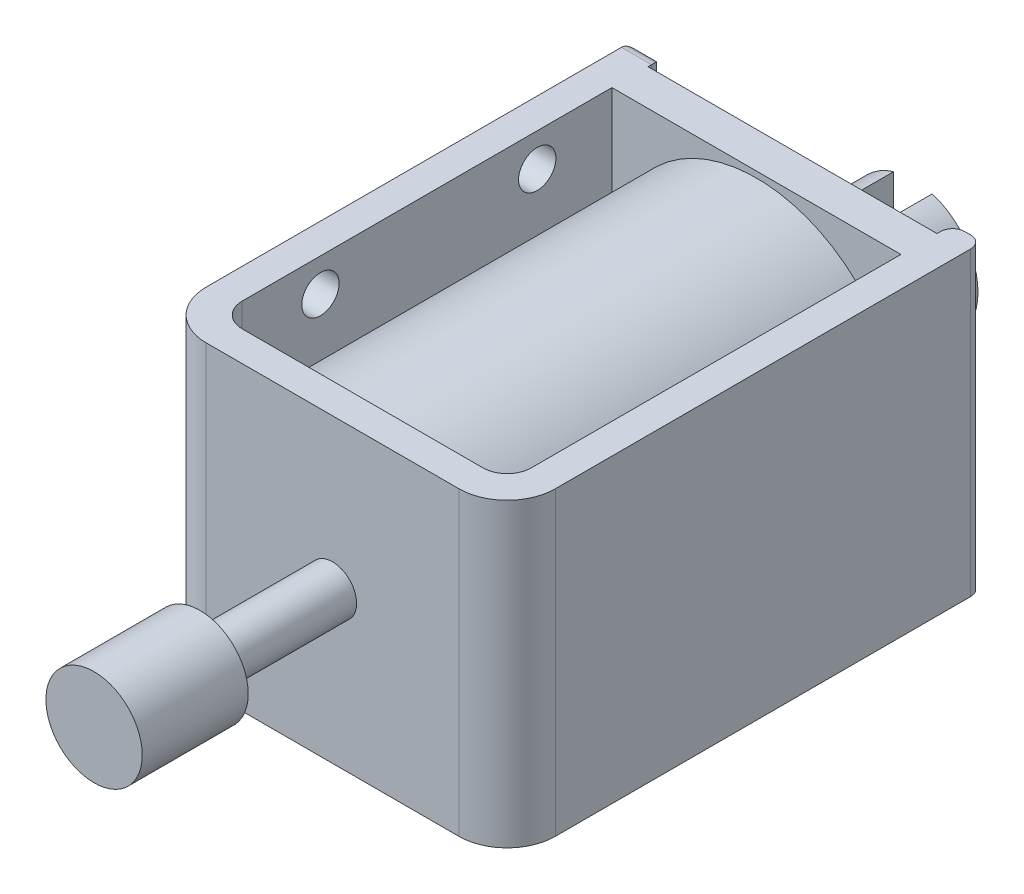
SolidWorks part; units mm, degrees
ref_plane "Front Plane" through (0, 0, 0) normal (0, 0, 1) x (1, 0, 0)
ref_plane "Top Plane" through (0, 0, 0) normal (0, 1, 0) x (1, 0, 0)
ref_plane "Right Plane" through (0, 0, 0) normal (1, 0, 0) x (0, 0, -1)
sketch "Sketch1" plane through (0, 0, 0) normal (0, 1, 0) x (1, 0, 0)
  line L0 (-21.1094, 9.1992) -> (-18.6094, 9.1992)
  line L1 (-18.6094, 9.1992) -> (-18.6094, 7.9023)
  line L2 (-18.6094, 7.9023) -> (5.3906, 7.9023)
  line L3 (5.3906, 7.9023) -> (5.3906, 9.1992)
  line L4 (5.3906, 9.1992) -> (7.8906, 9.1992)
  line L5 (7.8906, 9.1992) -> (7.8906, -30.3008)
  line L6 (7.8906, -30.3008) -> (-21.1094, -30.3008)
  line L7 (-21.1094, -30.3008) -> (-21.1094, 9.1992)
  line L8 (-18.6094, 4.9023) -> (5.3906, 4.9023)
  line L11 (-18.6094, 4.9023) -> (-18.6094, -27.8008)
  line L12 (-18.6094, -27.8008) -> (5.3906, -27.8008)
  line L13 (5.3906, -27.8008) -> (5.3906, 4.9023)
  dimension "D1" = 2.5
  dimension "D2" = 39.5
  dimension "D3" = 29
  dimension "D4" = 2.5
  dimension "D5" = 3
  dimension "D6" = 2.5
  dimension "D7" = 39.5
extrude "Boss-Extrude1" add sketch "Sketch1" along normal blind 25
sketch "Sketch3" plane through (0, 0, -4.9023) normal (0, 0, 1) x (1, 0, 0)
  line L0 (-6.6094, 25) -> (-6.6094, 0) construction
  line L1 (-21.1094, 25) -> (7.8906, 25) construction
  line L2 (-21.1094, 0) -> (7.8906, 0) construction
  circle A0 centre (-6.6094, 12.5) radius 12
  dimension "D1" = 24
extrude "Boss-Extrude7" add sketch "Sketch3" along normal up to surface (32.7031 mm away) separate body up to face at (-6.6094, 12.5, 27.8008)
sketch "Sketch4" plane through (0, 0, 30.3008) normal (0, 0, 1) x (1, 0, 0)
  line L0 (-21.1094, 25) -> (7.8906, 0) construction
  line L1 (-21.1094, 0) -> (7.8906, 0) construction
  line L2 (7.8906, 25) -> (-21.1094, 0) construction
  line L3 (-21.1094, 25) -> (-21.1094, 0) construction
  circle A0 centre (-6.6094, 12.5) radius 2
extrude "Boss-Extrude8" add sketch "Sketch4" along normal blind 11
sketch "Sketch5" plane through (0, 0, 41.3008) normal (0, 0, 1) x (1, 0, 0)
  circle A0 centre (-6.6094, 12.5) radius 4
extrude "Boss-Extrude9" add sketch "Sketch5" along normal blind 8.8
sketch "Sketch6" plane through (-21.1094, 0, 0) normal (-1, 0, 0) x (0, 0, 1)
  line L1 (19.3008, 2.75) -> (19.3008, 22.25) construction
  line L2 (-9.1992, 12.5) -> (30.3008, 12.5) construction
  line L3 (-9.1992, 25) -> (-9.1992, 0) construction
  line L4 (30.3008, 25) -> (30.3008, 0) construction
  line L5 (1.3008, 2.75) -> (1.3008, 22.25) construction
  circle A0 centre (1.3008, 2.75) radius 1.55
  circle A1 centre (1.3008, 22.25) radius 1.55
  circle A2 centre (19.3008, 22.25) radius 1.55
  circle A3 centre (19.3008, 2.75) radius 1.55
  point P14 (19.3008, 12.5)
  point P15 (1.3008, 12.5)
  dimension "D1" = 3.1
  dimension "D2" = 3.1
  dimension "D3" = 3.1
  dimension "D4" = 3.1
  dimension "D6" = 0
  dimension "D7" = 19.5
  dimension "D8" = 0
  dimension "D9" = 18
  dimension "D10" = 29
  dimension "D5" = 19.5
extrude "Cut-Extrude1" cut sketch "Sketch6" against normal up to surface (2.5 mm away) up to face at (-18.6094, 12.5, 11.4492)
sketch "Sketch7" plane through (0, 0, -7.9023) normal (0, 0, -1) x (-1, 0, 0)
  line L0 (-5.3906, 25) -> (18.6094, 0) construction
  line L1 (-5.3906, 0) -> (18.6094, 25) construction
  circle A0 centre (6.6094, 12.5) radius 5.4
extrude "Boss-Extrude10" add sketch "Sketch7" along normal blind 10
sketch "Sketch8" plane through (0, 0, -17.9023) normal (0, 0, -1) x (-1, 0, 0)
  line L0 (6.6094, 12.5) -> (6.6094, 17.9) construction
  line L1 (6.6094, 6.5716) -> (8.2094, 6.5716)
  line L2 (8.2094, 6.5716) -> (8.2094, 21.1415)
  line L3 (8.2094, 21.1415) -> (5.0094, 21.1415)
  line L4 (5.0094, 21.1415) -> (5.0094, 6.5716)
  line L5 (5.0094, 6.5716) -> (6.6094, 6.5716)
  dimension "D1" = 1.6
extrude "Cut-Extrude2" cut sketch "Sketch8" against normal blind 9
sketch "Sketch10" plane through (-5.0094, 0, 0) normal (-1, 0, 0) x (0, 0, 1)
  line L0 (-17.9023, 12.5) -> (-13.9023, 12.5) construction
  line L1 (-17.9023, 17.6575) -> (-17.9023, 7.3425) construction
  circle A0 centre (-13.9023, 12.5) radius 1.6
extrude "Cut-Extrude3" cut sketch "Sketch10" against normal blind 9 and the other way blind 9
fillet "Fillet1" radius 4 2 edges at (-21.1094, 12.5, 30.3008) (7.8906, 12.5, 30.3008)
fillet "Fillet2" radius 2 2 edges at (-18.6094, 12.5, 27.8008) (5.3906, 12.5, 27.8008)
fillet "Fillet3" radius 1 6 edges at (-18.6094, 12.5, -9.1992) (-19.8594, 25, -9.1992) (-21.1094, 12.5, -9.1992) (-19.8594, 0, -9.1992) (5.3906, 12.5, -9.1992) (7.8906, 12.5, -9.1992)
sketch "Sketch11" plane through (-21.1094, 0, 0) normal (-1, 0, 0) x (0, 0, 1)
  line L0 (19.3008, 22.25) -> (-13.9023, 12.5)
  line L1 (-13.9023, 12.5) -> (19.3008, 2.75)
